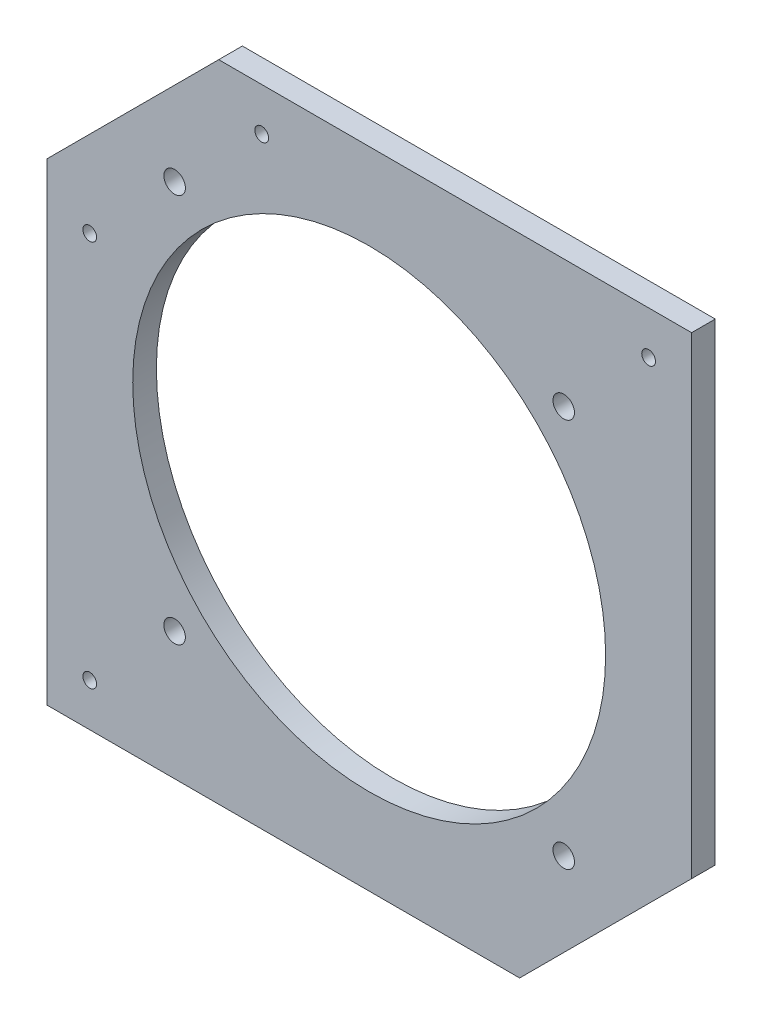
SolidWorks part; units mm, degrees
ref_plane "正面" through (0, 0, 0) normal (0, 0, 1) x (1, 0, 0)
ref_plane "平面" through (0, 0, 0) normal (0, 1, 0) x (1, 0, 0)
ref_plane "右側面" through (0, 0, 0) normal (1, 0, 0) x (0, 0, -1)
sketch "ｽｹｯﾁ1" plane through (0, 0, 0) normal (0, 0, 1) x (1, 0, 0)
  line L1 (-75, 75) -> (75, 75)
  line L2 (-75, 75) -> (-75, -75)
  line L3 (-75, -75) -> (75, -75)
  line L4 (75, 75) -> (75, -75)
  line L5 (-75, 75) -> (75, -75) construction
  line L6 (-75, -75) -> (75, 75) construction
  point P0 (0, 0)
  dimension "D1" = 150
extrude "ﾎﾞｽ - 押し出し1" add sketch "ｽｹｯﾁ1" along normal blind 5.5
sketch "ｽｹｯﾁ2" plane through (0, 0, 0) normal (0, 0, -1) x (-1, 0, 0)
  circle A2 centre (-45.2548, -45.2548) radius 2.5 construction
  circle A3 centre (-45.2548, -45.2548) radius 2.5
extrude "ｶｯﾄ - 押し出し1" cut sketch "ｽｹｯﾁ2" against normal through all both and the other way through all
sketch "ｽｹｯﾁ3" plane through (0, 0, 0) normal (0, 0, -1) x (-1, 0, 0)
  circle A6 centre (0, 0) radius 55
  circle A7 centre (0, 0) radius 55
  dimension "D1" = 15
extrude "ｶｯﾄ - 押し出し2" cut sketch "ｽｹｯﾁ3" against normal through all both
pattern_circular "円形ﾊﾟﾀｰﾝ1" count 4 over 360 about axis through (0, 0, 0) along (0, 0, 1) of "ｶｯﾄ - 押し出し1"
sketch "ｽｹｯﾁ4" plane through (0, 0, 0) normal (0, 0, -1) x (-1, 0, 0)
  line L0 (75, -75) -> (-75, -75) construction
  line L1 (75, 75) -> (75, -75) construction
  circle A0 centre (65, -65) radius 1.6
  dimension "D1" = 3.2
  dimension "D2" = 10
  dimension "D3" = 10
extrude "ｶｯﾄ - 押し出し3" cut sketch "ｽｹｯﾁ4" against normal through all both
chamfer "面取り1" distance 40 angle 45 1 edges at (-75, 75, 2.75)
chamfer "面取り2" distance 40 angle 45 1 edges at (75, -75, 2.75)
pattern_linear "直線ﾊﾟﾀｰﾝ1" count 2 spacing 90 along (0, 1, 0) of "ｶｯﾄ - 押し出し3"
ref_plane "平面1" through (0, 0, 0) normal (-0.7071, -0.7071, 0) x (-0.7071, 0.7071, 0)
mirror "ﾐﾗｰ1" about plane through (0, 0, 0) normal (-0.7071, -0.7071, 0) of "ｶｯﾄ - 押し出し3"
pattern_linear "直線ﾊﾟﾀｰﾝ2" count 2 spacing 90 along (-1, 0, 0) of "ﾐﾗｰ1"
